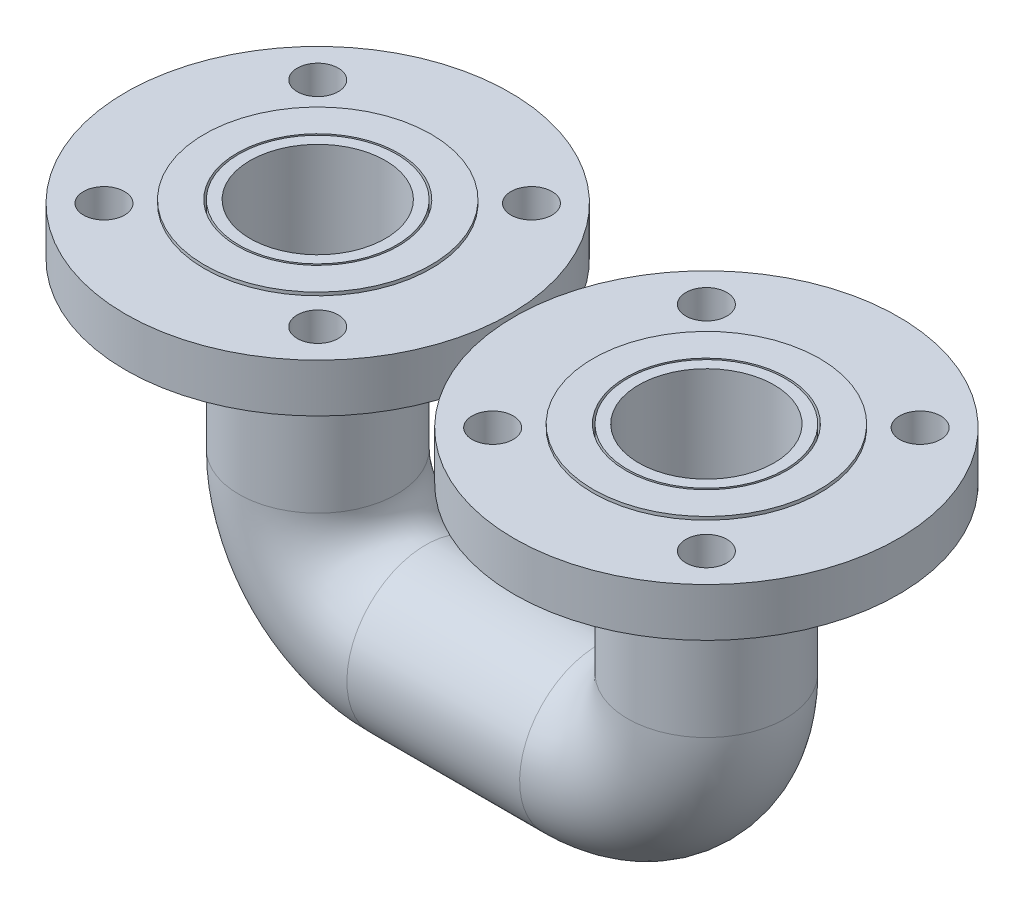
SolidWorks part; units mm, degrees
ref_plane "Front Plane" through (0, 0, 0) normal (0, 0, 1) x (1, 0, 0)
ref_plane "Top Plane" through (0, 0, 0) normal (0, 1, 0) x (1, 0, 0)
ref_plane "Right Plane" through (0, 0, 0) normal (1, 0, 0) x (0, 0, -1)
sketch "Sketch1" plane through (0, 0, 0) normal (0, 1, 0) x (1, 0, 0)
  line L0 (0, 0) -> (-50000, 0) construction
  line L1 (0, 0) -> (0, 50000) construction
  circle A0 centre (0, 0) radius 89
  circle A1 centre (0, 0) radius 37.35
  circle A2 centre (0, 0) radius 70 construction
  circle A3 centre (-49.4975, 49.4975) radius 9.5
  circle A4 centre (-49.4975, -49.4975) radius 9.5
  circle A5 centre (49.4975, -49.4975) radius 9.5
  circle A6 centre (49.4975, 49.4975) radius 9.5
  dimension "D1" = 178
  dimension "D2" = 74.7
  dimension "D3" = 140
  dimension "D5" = 19
extrude "Boss-Extrude1" add sketch "Sketch1" along normal blind 22.4
sketch "Sketch2" plane through (0, 22.4, 0) normal (0, 1, 0) x (1, 0, 0)
  circle A0 centre (0, 0) radius 52.5
  circle A1 centre (0, 0) radius 37.35
  dimension "D1" = 105
extrude "Boss-Extrude2" add sketch "Sketch2" along normal blind 1.5
ref_plane "Plane1" through (90, 0, 0) normal (1, 0, 0) x (0, 0, -1)
mirror "Mirror3" about plane through (90, 0, 0) normal (1, 0, 0) of bodies 116
sketch "Sketch3" plane through (0, 0, 0) normal (0, 0, 1) x (1, 0, 0)
  line L0 (0, -76.1) -> (0, 23.9)
  line L1 (50, -126.1) -> (130, -126.1)
  line L2 (180, -76.1) -> (180, 23.9)
  line L4 (52.5, 23.9) -> (-52.5, 23.9) construction
  line L5 (217.35, 23.9) -> (142.65, 23.9) construction
  arc A0 (50, -126.1) -> (0, -76.1) centre (50, -76.1) cw
  arc A1 (130, -126.1) -> (180, -76.1) centre (130, -76.1) ccw
  dimension "D1" = 50
  dimension "D2" = 100
ref_plane "Plane3" through (0, 23.9, 0) normal (0, 1, 0) x (1, 0, 0)
sketch "Sketch5" plane through (0, 23.9, 0) normal (0, 1, 0) x (1, 0, 0)
  circle A0 centre (0, 0) radius 36.5
  circle A1 centre (0, 0) radius 31.34
  dimension "D1" = 73
  dimension "D2" = 5.16
sweep "Sweep2" add profiles "Sketch5" path "Sketch3"
